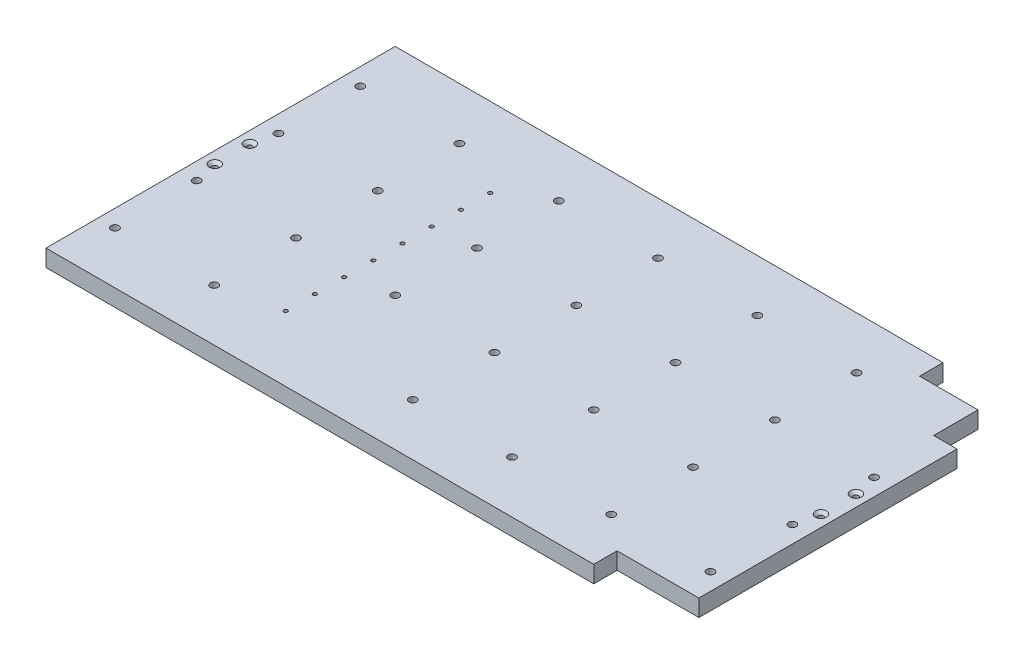
SolidWorks part; units mm, degrees
ref_plane "Front Plane" through (0, 0, 0) normal (0, 0, 1) x (1, 0, 0)
ref_plane "Top Plane" through (0, 0, 0) normal (0, 1, 0) x (1, 0, 0)
ref_plane "Right Plane" through (0, 0, 0) normal (1, 0, 0) x (0, 0, -1)
sketch "Sketch1" plane through (0, 0, 0) normal (0, 1, 0) x (1, 0, 0)
  line L1 (269.5, -149.5) -> (-269.5, -149.5)
  line L2 (269.5, -149.5) -> (269.5, 149.5)
  line L3 (269.5, 149.5) -> (-269.5, 149.5)
  line L4 (-269.5, -149.5) -> (-269.5, 149.5)
  line L5 (269.5, -149.5) -> (-269.5, 149.5) construction
  line L6 (269.5, 149.5) -> (-269.5, -149.5) construction
  point P0 (0, 0)
  dimension "D1" = 299
  dimension "D2" = 539
extrude "Boss-Extrude1" add sketch "Sketch1" against normal blind 14.5
sketch "Sketch22" plane through (0, 0, 0) normal (0, 1, 0) x (1, 0, 0)
  line L0 (269.5, 149.5) -> (199.5, 149.5)
  line L1 (269.5, 149.5) -> (-269.5, 149.5) construction
  line L2 (199.5, 149.5) -> (199.5, 129.5)
  line L3 (199.5, 129.5) -> (249.5, 129.5)
  line L4 (249.5, 129.5) -> (249.5, 91.5)
  line L5 (249.5, 91.5) -> (269.5, 91.5)
  line L6 (269.5, -149.5) -> (269.5, 149.5) construction
  line L7 (269.5, 91.5) -> (269.5, 149.5)
  line L9 (269.5, -149.5) -> (199.5, -149.5)
  line L10 (269.5, -149.5) -> (269.5, -129.5)
  line L11 (269.5, -129.5) -> (199.5, -129.5)
  line L12 (199.5, -149.5) -> (199.5, -129.5)
  dimension "D1" = 20
  dimension "D2" = 20
  dimension "D3" = 20
  dimension "D4" = 70
  dimension "D5" = 70
  dimension "D6" = 58
extrude "Cut-Extrude9" cut sketch "Sketch22" against normal through all
sketch "cell" plane through (0, -14.5, 0) normal (0, -1, 0) x (1, 0, 0)
  line L12 (-129.5, -62.4) -> (-100.5, -62.4)
  line L13 (-129.5, -15.9) -> (-129.5, -62.4)
  line L14 (-100.5, -15.9) -> (-129.5, -15.9)
  line L15 (-100.5, 15.9) -> (-100.5, -15.9)
  line L16 (-129.5, 15.9) -> (-100.5, 15.9)
  line L17 (-129.5, 62.4) -> (-129.5, 15.9)
  line L18 (-100.5, 62.4) -> (-129.5, 62.4)
  line L19 (-100.5, 84) -> (-100.5, 62.4)
  line L20 (128.5, 84) -> (-100.5, 84)
  line L21 (128.5, -84) -> (128.5, 84)
  line L22 (-100.5, -84) -> (128.5, -84)
  line L23 (-100.5, -62.4) -> (-100.5, -84)
  line L24 (-129.5, -62.4) -> (-100.5, -62.4)
  line L25 (-129.5, -15.9) -> (-129.5, -62.4)
  line L26 (-100.5, -15.9) -> (-129.5, -15.9)
  line L27 (-100.5, 15.9) -> (-100.5, -15.9)
  line L28 (-129.5, 15.9) -> (-100.5, 15.9)
  line L29 (-129.5, 62.4) -> (-129.5, 15.9)
  line L30 (-100.5, 62.4) -> (-129.5, 62.4)
  line L31 (-100.5, 84) -> (-100.5, 62.4)
  line L32 (128.5, 84) -> (-100.5, 84)
  line L33 (128.5, -84) -> (128.5, 84)
  line L34 (-100.5, -84) -> (128.5, -84)
  line L35 (-100.5, -62.4) -> (-100.5, -84)
  dimension "D1" = 0
sketch "Sketch2" plane through (0, -14.5, 0) normal (0, -1, 0) x (1, 0, 0)
  line L0 (-269.5, 0) -> (-260, 0) construction
  line L1 (-269.5, -149.5) -> (-269.5, 149.5) construction
  line L2 (0, 0) -> (0, 149.5) construction
  line L3 (-269.5, 149.5) -> (199.5, 149.5) construction
  line L4 (-234.5, -3) -> (-234.5, -89.5)
  line L5 (-234.5, -89.5) -> (-110.5, -89.5)
  line L6 (-110.5, -89.5) -> (-110.5, 93.5)
  line L7 (-89, 128.5) -> (178.5, 128.5)
  line L8 (228.5, 108.5) -> (228.5, -3)
  line L9 (234.5, 3) -> (234.5, 114.5)
  line L10 (184.5, 134.5) -> (-95, 134.5)
  line L11 (-130, 99.5) -> (-130, -83.5)
  line L12 (-130, -83.5) -> (-228.5, -83.5)
  line L13 (-228.5, -83.5) -> (-228.5, 3)
  line L14 (199.5, -149.5) -> (-269.5, -149.5) construction
  line L15 (-260, -3) -> (-234.5, -3)
  line L16 (128.5, -84) -> (128.5, 84)
  line L17 (-100.5, -84) -> (128.5, -84)
  line L18 (-100.5, -62.4) -> (-100.5, -84)
  line L19 (-129.5, -62.4) -> (-100.5, -62.4)
  line L20 (-129.5, -15.9) -> (-129.5, -62.4)
  line L21 (-100.5, -15.9) -> (-129.5, -15.9)
  line L22 (-100.5, 15.9) -> (-100.5, -15.9)
  line L23 (-129.5, 15.9) -> (-100.5, 15.9)
  line L24 (-129.5, 62.4) -> (-129.5, 15.9)
  line L25 (-100.5, 62.4) -> (-129.5, 62.4)
  line L26 (-100.5, 84) -> (-100.5, 62.4)
  line L27 (128.5, 84) -> (-100.5, 84)
  line L28 (128.5, -84) -> (128.5, 84) construction
  line L29 (-100.5, -84) -> (128.5, -84) construction
  line L30 (-100.5, -62.4) -> (-100.5, -84) construction
  line L31 (-129.5, -62.4) -> (-100.5, -62.4) construction
  line L32 (-129.5, -15.9) -> (-129.5, -62.4) construction
  line L33 (-100.5, -15.9) -> (-129.5, -15.9) construction
  line L34 (-100.5, 15.9) -> (-100.5, -15.9) construction
  line L35 (-129.5, 15.9) -> (-100.5, 15.9) construction
  line L36 (-129.5, 62.4) -> (-129.5, 15.9) construction
  line L37 (-100.5, 62.4) -> (-129.5, 62.4) construction
  line L38 (-100.5, 84) -> (-100.5, 62.4) construction
  line L39 (128.5, 84) -> (-100.5, 84) construction
  line L40 (-228.5, 3) -> (-260, 3)
  line L41 (260, 0) -> (269.5, 0) construction
  line L42 (269.5, 129.5) -> (269.5, -91.5) construction
  line L43 (234.5, 3) -> (260, 3)
  line L44 (228.5, -3) -> (260, -3)
  line L45 (-128, -58.7) -> (-128, -19.5) construction
  line L46 (-130, 99.5) -> (-95, 99.5)
  line L47 (-95, 99.5) -> (-95, 134.5)
  line L48 (-89, 128.5) -> (-89, 93.5)
  line L49 (-89, 93.5) -> (-110.5, 93.5)
  line L50 (184.5, 134.5) -> (184.5, 114.5)
  line L51 (184.5, 114.5) -> (234.5, 114.5)
  line L52 (178.5, 128.5) -> (178.5, 108.5)
  line L53 (178.5, 108.5) -> (228.5, 108.5)
  line L56 (269.5, 129.5) -> (199.5, 129.5) construction
  line L59 (199.5, 129.5) -> (199.5, 149.5) construction
  arc A2 (-260, 3) -> (-260, -3) centre (-260, 0) ccw
  arc A3 (260, -3) -> (260, 3) centre (260, 0) ccw
  dimension "D1" = 6
  dimension "D12" = 6
  dimension "D2" = 9.5
  dimension "D4" = 6
  dimension "D5" = 10
  dimension "D6" = 2
  dimension "D7" = 6
  dimension "D8" = 60
  dimension "D9" = 15
  dimension "D10" = 6
  dimension "D11" = 35
  dimension "D13" = 9.5
  dimension "D14" = 6
  dimension "D15" = 35
  dimension "D16" = 6
  dimension "D17" = 6
  dimension "D18" = 50
  dimension "D19" = 35
  dimension "D20" = 6
  dimension "D21" = 6
  dimension "D22" = 15
  dimension "D23" = 15
  dimension "D3" = 0
extrude "Cut-Extrude1" cut sketch "Sketch2" against normal blind 6
sketch "Sketch6" plane through (0, 0, 0) normal (0, 1, 0) x (1, 0, 0)
  line L0 (-269.5, 0) -> (-259.5, 0) construction
  line L1 (-269.5, 149.5) -> (-269.5, -149.5) construction
  line L2 (-259.5, 0) -> (-259.5, 15) construction
  dimension "D1" = 10
  dimension "D2" = 15
hole_wizard "CSK for M4 Countersunk Flat Head1" positions "3DSketch1" profile "Sketch7" countersink size "M4" standard "BSI" end condition through all
sketch3d "3DSketch1"
  point P0 (-259.5, 0, -15)
sketch "Sketch7" plane through (-259.5, 0, -15) normal (1, 0, 0) x (0, 0, 1)
  line L0 (0, 0) -> (0, 14.5)
  line L1 (0, 14.5) -> (2.25, 14.5)
  line L2 (2.25, 14.5) -> (2.25, 2.45)
  line L3 (2.25, 2.45) -> (4.7, 0)
  line L5 (4.7, 0) -> (0, 0)
  line L6 (-2.25, 2.45) -> (-4.7, 0) construction
  line L11 (0, -6.35) -> (0, 107.95) construction
  dimension "Thru Hole Dia." = 4.5
  dimension "Thru Hole Depth" = 14.5
  dimension "Near C'Sink Dia." = 9.4
  dimension "Near C'Sink Angle" = 90
mirror "Mirror1" about plane through (0, 0, 0) normal (0, 0, 1) of "CSK for M4 Countersunk Flat Head1"
mirror "Mirror2" about plane through (0, 0, 0) normal (1, 0, 0) of "CSK for M4 Countersunk Flat Head1", "Mirror1"
sketch "Sketch11" plane through (0, -14.5, 0) normal (0, -1, 0) x (1, 0, 0)
  line L0 (-100.5, -84) -> (128.5, -84) construction
  line L1 (128.5, -84) -> (128.5, 84) construction
  line L2 (128.5, 84) -> (-100.5, 84) construction
  line L3 (-100.5, -84) -> (128.5, -84)
  line L4 (128.5, -84) -> (128.5, 84)
  line L5 (128.5, 84) -> (-100.5, 84)
  line L6 (-100.5, 84) -> (-100.5, -84)
extrude "Cut-Extrude4" cut sketch "Sketch11" against normal blind 2.245
sketch "Sketch12" plane through (0, -12.255, 0) normal (0, -1, 0) x (1, 0, 0)
  line L0 (-100.5, -84) -> (128.5, -84) construction
  line L1 (-100.5, 84) -> (-83.5, 84)
  line L2 (-100.5, 84) -> (-100.5, -84)
  line L3 (-100.5, -84) -> (-83.5, -84)
  line L4 (-83.5, 84) -> (-83.5, -84)
  dimension "D1" = 17
extrude "Boss-Extrude2" add sketch "Sketch12" along normal blind 1.67
sketch "purge holes" plane through (0, 0, 0) normal (0, 1, 0) x (1, 0, 0)
  point P0 (-255, -105)
  point P1 (-170, -105)
  point P5 (-85, -105)
  point P6 (0, -105)
  point P7 (85, -105)
  point P8 (170, -105)
  point P9 (255, -105)
  point P10 (-170, -35)
  point P11 (-85, -35)
  point P12 (0, -35)
  point P13 (85, -35)
  point P14 (170, -35)
  point P15 (255, -35)
  point P16 (-170, 35)
  point P17 (-85, 35)
  point P18 (0, 35)
  point P19 (85, 35)
  point P20 (170, 35)
  point P21 (255, 35)
  point P22 (-170, 105)
  point P23 (-85, 105)
  point P24 (0, 105)
  point P25 (85, 105)
  point P26 (170, 105)
  point P27 (255, 105)
  point P28 (-255, -35)
  point P29 (-255, 35)
  point P30 (-255, 105)
  dimension "D1" = 255
  dimension "D2" = 105
  dimension "D5" = 70
  dimension "D6" = 85
  dimension "D3" = 7
  dimension "D4" = 4
hole_wizard "M6 Clearance Hole1" positions "3DSketch3" profile "Sketch15" hole size "M6" standard "ANSI Metric" end condition through all
sketch3d "3DSketch3"
  point P0 (-255, 0, -105)
  point P3 (-255, 0, -35)
  point P6 (-255, 0, 35)
  point P9 (-255, 0, 105)
  point P12 (-170, 0, 105)
  point P15 (-170, 0, 35)
  point P18 (-170, 0, -35)
  point P21 (-170, 0, -105)
  point P24 (-85, 0, -105)
  point P27 (0, 0, -105)
  point P30 (85, 0, -105)
  point P33 (170, 0, -105)
  point P39 (255, 0, -35)
  point P42 (255, 0, 35)
  point P45 (255, 0, 105)
  point P48 (170, 0, 105)
  point P51 (170, 0, 35)
  point P54 (170, 0, -35)
  point P57 (85, 0, 105)
  point P60 (0, 0, 105)
  point P66 (0, 0, 35)
  point P69 (0, 0, -35)
  point P72 (85, 0, -35)
  point P75 (85, 0, 35)
  point P78 (-85, 0, 35)
  point P81 (-85, 0, -35)
sketch "Sketch15" plane through (-255, 0, -105) normal (1, 0, 0) x (0, 0, 1)
  line L0 (0, 0) -> (0, 14.5)
  line L1 (0, 14.5) -> (3.3, 14.5)
  line L2 (3.3, 14.5) -> (3.3, 0)
  line L5 (3.3, 0) -> (0, 0)
  line L11 (0, -6.35) -> (0, 107.95) construction
  dimension "Thru Hole Dia." = 6.6
  dimension "Thru Hole Depth" = 14.5
sketch "Sketch17" plane through (0, -8.5, 0) normal (0, -1, 0) x (-1, 0, 0)
  line L0 (110.5, -99.5) -> (130, -99.5) construction
  line L1 (110.5, 89.5) -> (110.5, -93.5) construction
  line L2 (130, -99.5) -> (130, 83.5) construction
  line L3 (120.25, -99.5) -> (120.25, 89.5) construction
  line L4 (234.5, 89.5) -> (110.5, 89.5) construction
  line L5 (95, -99.5) -> (130, -99.5) construction
  point P13 (120.25, 81.5)
  dimension "D1" = 8
hole_wizard "M4x0.7 Tapped Hole1" positions "3DSketch4" profile "Sketch18" tap size "M4x0.7" standard "ANSI Metric" end condition through all
sketch3d "3DSketch4"
  point P0 (-120.25, -8.5, -81.5)
sketch "Sketch18" plane through (-120.25, -8.5, -81.5) normal (1, 0, 0) x (0, 0, -1)
  line L0 (0, 0) -> (0, 8.5)
  line L1 (0, 8.5) -> (1.65, 8.5)
  line L2 (1.65, 8.5) -> (1.65, 0)
  line L5 (1.65, 0) -> (0, 0)
  line L11 (0, -6.35) -> (0, 107.95) construction
  dimension "Thru Tap Drill Dia." = 3.3
  dimension "Thru Tap Drill Depth" = 8.5
pattern_linear "LPattern1" count 8 spacing 25 along (0, 0, 1) of "M4x0.7 Tapped Hole1"
sketch "Sketch19" plane through (0, -14.5, 0) normal (0, -1, 0) x (1, 0, 0)
  line L0 (128.5, 84) -> (-83.5, 84) construction
  line L1 (22.5, 84) -> (22.5, -149.5) construction
  line L2 (199.5, -149.5) -> (-269.5, -149.5) construction
  line L3 (22.5, -84) -> (-83.5, -84) construction
  line L4 (-83.5, -84) -> (128.5, -84) construction
  line L5 (-30.5, -84) -> (-30.5, 84) construction
  line L6 (22.5, -84) -> (128.5, -84) construction
  line L7 (75.5, -84) -> (75.5, 84) construction
  line L8 (118.5, 0) -> (-100.5, 0) construction
  line L9 (-100.5, 84) -> (-100.5, -84) construction
  line L10 (-73.5, 84) -> (-73.5, -84) construction
  line L11 (118.5, 84) -> (118.5, -84) construction
  line L12 (-83.5, -84) -> (-83.5, -37.9394) construction
  line L13 (128.5, -84) -> (128.5, 84) construction
  line L14 (-73.5, -84) -> (-73.5, -149.5) construction
  line L15 (-30.5, -84) -> (-30.5, -149.5) construction
  line L16 (75.5, -84) -> (75.5, -149.5) construction
  line L17 (118.5, -84) -> (118.5, -149.5) construction
  dimension "D1" = 10
  dimension "D2" = 10
sketch "Sketch20" plane through (0, -12.255, 0) normal (0, -1, 0) x (1, 0, 0)
  line L6 (-73.5, 84) -> (-73.5, -84) construction
  line L7 (118.5, 0) -> (-100.5, 0) construction
  line L9 (-30.5, -84) -> (-30.5, 84) construction
  line L12 (22.5, 84) -> (22.5, -149.5) construction
  line L16 (75.5, -84) -> (75.5, 84) construction
  line L21 (118.5, 84) -> (118.5, -84) construction
  line L43 (118.5, 84) -> (118.5, -84) construction
  line L44 (75.5, -84) -> (75.5, 84) construction
  line L45 (22.5, 84) -> (22.5, -149.5) construction
  line L46 (118.5, 0) -> (-100.5, 0) construction
  line L47 (-30.5, -84) -> (-30.5, 84) construction
  line L48 (-73.5, 84) -> (-73.5, -84) construction
  line L49 (128.5, 84) -> (-83.5, 84) construction
  line L50 (-63.5, -84) -> (-83.5, -84)
  line L51 (-63.5, -84) -> (-63.5, -10)
  line L52 (-63.5, 84) -> (-83.5, 84)
  line L53 (-83.5, -84) -> (-83.5, -10)
  line L54 (-63.5, -84) -> (-83.5, 84) construction
  line L55 (-63.5, 84) -> (-83.5, -84) construction
  line L56 (-20.5, -84) -> (-40.5, -84)
  line L57 (-20.5, -84) -> (-20.5, -10)
  line L58 (-20.5, 84) -> (-40.5, 84)
  line L59 (-40.5, -84) -> (-40.5, -10)
  line L60 (-20.5, -84) -> (-40.5, 84) construction
  line L61 (-20.5, 84) -> (-40.5, -84) construction
  line L62 (118.5, 10) -> (117.3095, 10)
  line L63 (32.5, -84) -> (12.5, -84)
  line L64 (32.5, -84) -> (32.5, -10)
  line L65 (32.5, 84) -> (12.5, 84)
  line L66 (12.5, -84) -> (12.5, -10)
  line L67 (32.5, -84) -> (12.5, 84) construction
  line L68 (32.5, 84) -> (12.5, -84) construction
  line L69 (85.5, -84) -> (65.5, -84)
  line L70 (85.5, -84) -> (85.5, -10)
  line L71 (85.5, 84) -> (65.5, 84)
  line L72 (65.5, -84) -> (65.5, -10)
  line L73 (85.5, -84) -> (65.5, 84) construction
  line L74 (85.5, 84) -> (65.5, -84) construction
  line L75 (128.5, -84) -> (108.5, -84)
  line L76 (128.5, -84) -> (128.5, 84)
  line L77 (128.5, 84) -> (108.5, 84)
  line L78 (108.5, -84) -> (108.5, -10)
  line L79 (128.5, -84) -> (108.5, 84) construction
  line L80 (128.5, 84) -> (108.5, -84) construction
  line L81 (118.5, -10) -> (117.3095, -10)
  line L82 (-83.5, 10) -> (-83.5, 84)
  line L84 (118.5, -10) -> (-100.5, -10) construction
  line L85 (-72.3095, -10) -> (-74.6905, -10)
  line L86 (-63.5, 10) -> (-63.5, 84)
  line L87 (-40.5, 10) -> (-40.5, 84)
  line L88 (-40.5, -10) -> (-63.5, -10)
  line L89 (-29.3095, -10) -> (-31.6905, -10)
  line L90 (-20.5, 10) -> (-20.5, 84)
  line L91 (12.5, 10) -> (12.5, 84)
  line L92 (12.5, -10) -> (-20.5, -10)
  line L93 (32.5, 10) -> (32.5, 84)
  line L94 (23.6905, -10) -> (21.3095, -10)
  line L95 (65.5, 10) -> (65.5, 84)
  line L96 (65.5, -10) -> (32.5, -10)
  line L97 (76.6905, -10) -> (74.3095, -10)
  line L98 (85.5, 10) -> (85.5, 84)
  line L99 (108.5, 10) -> (108.5, 84)
  line L100 (108.5, -10) -> (85.5, -10)
  line L101 (108.5, 10) -> (85.5, 10)
  line L102 (118.5, 10) -> (-100.5, 10) construction
  line L103 (76.6905, 10) -> (74.3095, 10)
  line L104 (65.5, 10) -> (32.5, 10)
  line L105 (23.6905, 10) -> (21.3095, 10)
  line L106 (12.5, 10) -> (-20.5, 10)
  line L107 (-29.3095, 10) -> (-31.6905, 10)
  line L108 (-40.5, 10) -> (-63.5, 10)
  line L109 (-72.3095, 10) -> (-74.6905, 10)
  line L112 (-83.5, 10) -> (-83.5, -10)
  point P4 (-73.5, 0)
  point P11 (-30.5, 0)
  point P22 (22.5, 0)
  point P27 (75.5, 0)
  dimension "D1" = 20
  dimension "D2" = 20
  dimension "D3" = 20
  dimension "D4" = 20
  dimension "D5" = 10
  dimension "D6" = 10
extrude "Cut-Extrude5" cut sketch "Sketch20" against normal blind 1.5 contours L112 L53 L50 L51 L88 L59 L56 L57 L92 L66 L63 L64 L96 L72 L69 L70 L100 L78 L75 L76 L77 L99 L101 L98 L71 L95 L104 L93 L65 L91 L106 L90 L58 L87 L108 L86 L52 L82
sketch "Sketch21" plane through (0, -14.5, 0) normal (0, -1, 0) x (1, 0, 0)
  line L0 (-83.5, -84) -> (-63.5, -84)
  line L1 (-40.5, -84) -> (-20.5, -84)
  line L2 (-83.5, -85.5) -> (-63.5, -85.5)
  line L3 (-40.5, -85.5) -> (-20.5, -85.5)
  line L4 (12.5, -85.5) -> (32.5, -85.5)
  line L5 (65.5, -85.5) -> (85.5, -85.5)
  line L6 (108.5, -85.5) -> (128.5, -85.5)
  line L7 (128.5, -84) -> (108.5, -84)
  line L8 (85.5, -84) -> (65.5, -84)
  line L9 (32.5, -84) -> (12.5, -84)
  line L10 (-83.5, -84) -> (-83.5, -149.5)
  line L11 (-83.5, -84) -> (-83.5, -85.5)
  line L12 (-63.5, -84) -> (-63.5, -149.5)
  line L13 (-63.5, -84) -> (-63.5, -85.5)
  line L15 (-40.5, -84) -> (-40.5, -149.5)
  line L16 (-40.5, -84) -> (-40.5, -85.5)
  line L17 (-20.5, -84) -> (-20.5, -149.5)
  line L18 (-20.5, -84) -> (-20.5, -85.5)
  line L20 (12.5, 84) -> (12.5, -149.5)
  line L21 (12.5, -84) -> (12.5, -85.5)
  line L22 (32.5, 84) -> (32.5, -149.5)
  line L23 (32.5, -84) -> (32.5, -85.5)
  line L25 (65.5, -84) -> (65.5, -149.5)
  line L26 (65.5, -84) -> (65.5, -85.5)
  line L27 (85.5, -84) -> (85.5, -149.5)
  line L28 (85.5, -84) -> (85.5, -85.5)
  line L30 (108.5, -84) -> (108.5, -149.5)
  line L31 (108.5, -84) -> (108.5, -85.5)
  line L32 (128.5, -84) -> (128.5, -149.5)
  line L33 (128.5, -84) -> (128.5, -85.5)
  dimension "D11" = 1.5
  dimension "D1" = 10
  dimension "D2" = 10
  dimension "D3" = 10
  dimension "D4" = 10
  dimension "D5" = 10
  dimension "D6" = 10
  dimension "D7" = 10
  dimension "D8" = 10
  dimension "D9" = 10
  dimension "D10" = 10
extrude "Cut-Extrude8" cut sketch "Sketch21" against normal up to surface (3.745 mm away) up to face at (18.5, -10.755, 0)
sketch "Sketch23" plane through (0, 0, 0) normal (0, 1, 0) x (1, 0, 0)
  line L1 (-269.5, 149.5) -> (-254.5, 149.5)
  line L2 (-269.5, 149.5) -> (-269.5, 134.5)
  line L3 (-269.5, 134.5) -> (-254.5, 134.5)
  line L4 (-254.5, 149.5) -> (-254.5, 134.5)
  dimension "D1" = 15
  dimension "D2" = 15
